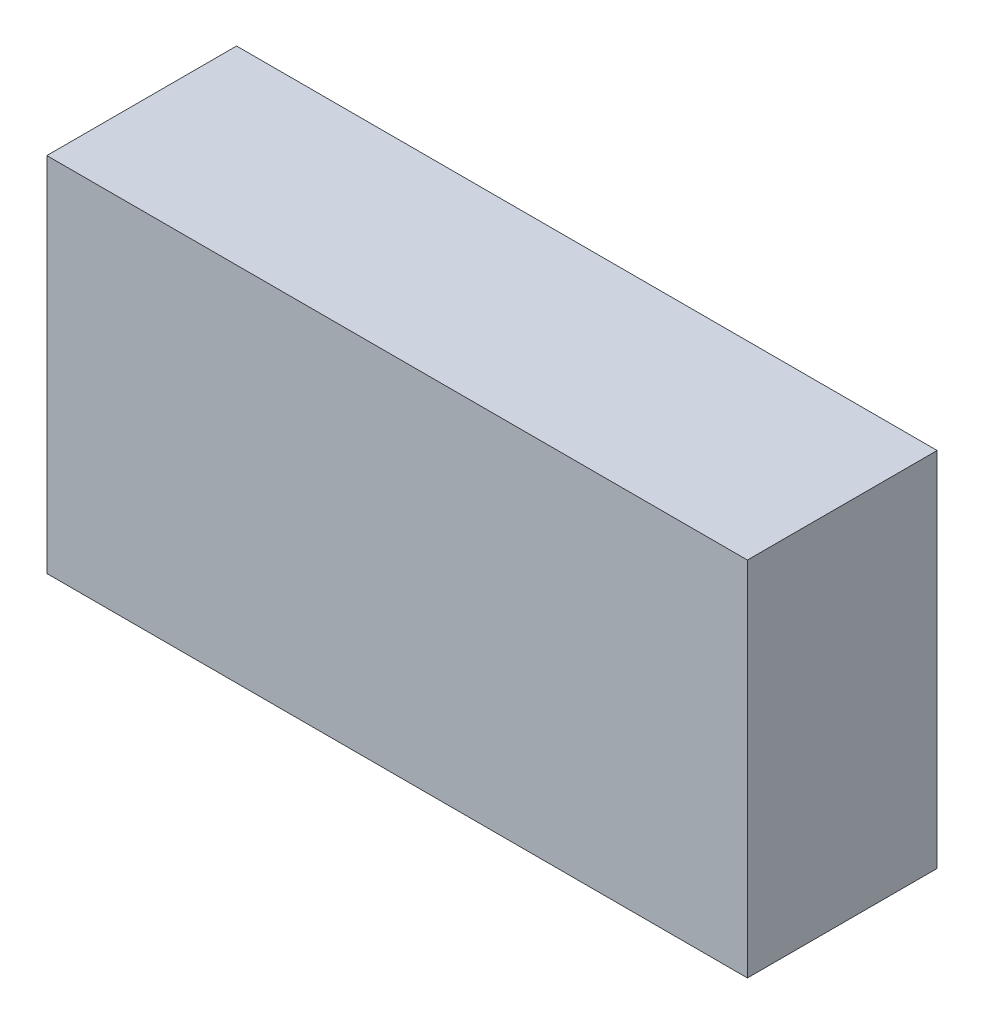
SolidWorks part; units mm, degrees
ref_plane "前视基准面" through (0, 0, 0) normal (0, 0, 1) x (1, 0, 0)
ref_plane "上视基准面" through (0, 0, 0) normal (0, 1, 0) x (1, 0, 0)
ref_plane "右视基准面" through (0, 0, 0) normal (1, 0, 0) x (0, 0, -1)
sketch "草图1" plane through (0, 0, 0) normal (0, 0, 1) x (1, 0, 0)
  line L1 (-57.1795, 75.5128) -> (182.8205, 75.5128)
  line L2 (-57.1795, 75.5128) -> (-57.1795, -48.4872)
  line L3 (-57.1795, -48.4872) -> (182.8205, -48.4872)
  line L4 (182.8205, 75.5128) -> (182.8205, -48.4872)
  dimension "D1" = 124
  dimension "D2" = 240
extrude "凸台-拉伸1" add sketch "草图1" along normal blind 65
